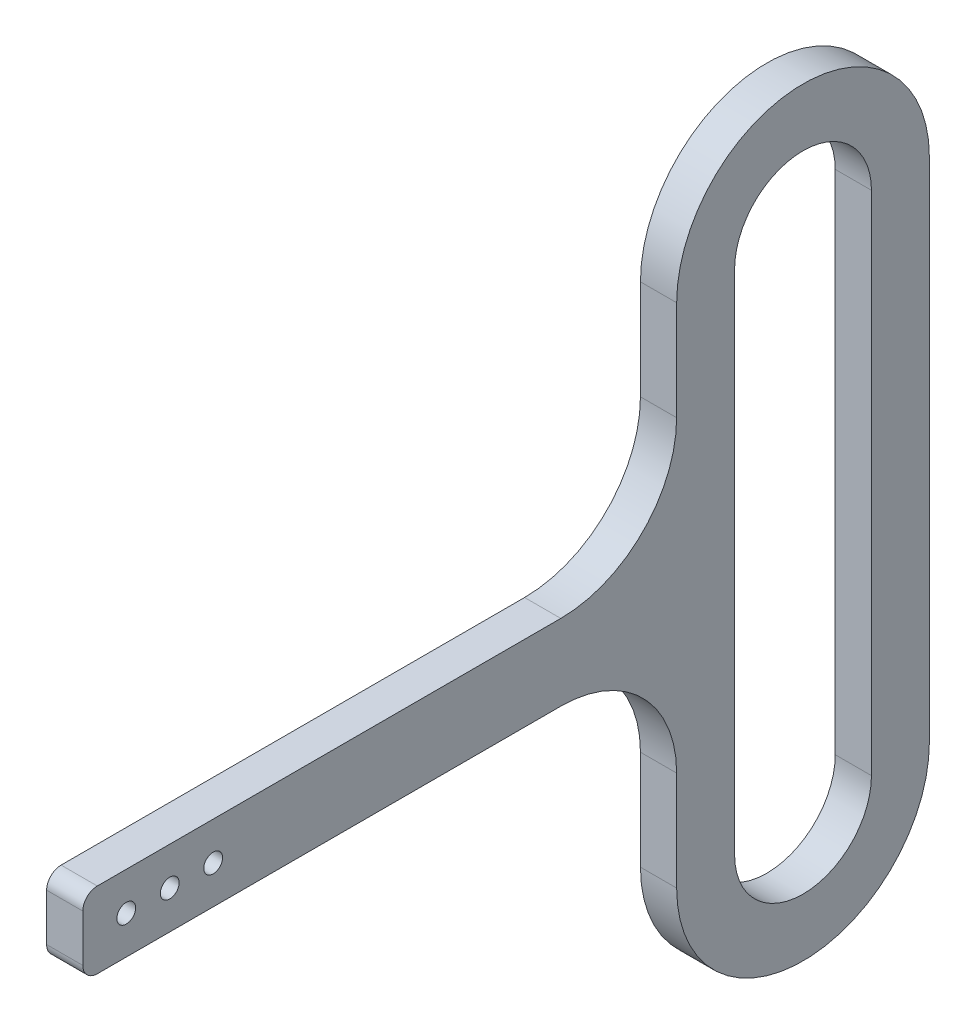
SolidWorks part; units mm, degrees
ref_plane "Front Plane" through (0, 0, 0) normal (0, 0, 1) x (1, 0, 0)
ref_plane "Top Plane" through (0, 0, 0) normal (0, 1, 0) x (1, 0, 0)
ref_plane "Right Plane" through (0, 0, 0) normal (1, 0, 0) x (0, 0, -1)
sketch "Sketch2" plane through (0, 0, 0) normal (1, 0, 0) x (0, 0, -1)
  line L0 (-22.16, -44.45) -> (-22.16, 44.45)
  line L1 (0, -44.45) -> (0, 44.45) construction
  line L2 (-12, -44.45) -> (-12, 44.45)
  line L3 (12, -44.45) -> (12, 44.45)
  line L4 (22.16, -44.45) -> (22.16, 44.45)
  line L5 (0, 0) -> (-80.0365, 0) construction
  line L6 (-22.16, -6.6675) -> (-126.3, -6.6675)
  line L7 (-22.16, 0) -> (-126.3, 0) construction
  line L8 (-22.16, 0) -> (-22.16, 6.6675)
  line L9 (-22.16, 6.6675) -> (-126.3, 6.6675)
  line L10 (-126.3, -6.6675) -> (-126.3, 6.6675)
  line L11 (-126.3, 0) -> (-118.68, 0) construction
  arc A0 (-12, -44.45) -> (12, -44.45) centre (0, -44.45) ccw
  arc A1 (12, 44.45) -> (-12, 44.45) centre (0, 44.45) ccw
  arc A2 (22.16, 44.45) -> (-22.16, 44.45) centre (0, 44.45) ccw
  arc A3 (-22.16, -44.45) -> (22.16, -44.45) centre (0, -44.45) ccw
  circle A4 centre (-118.68, 0) radius 1.651
  circle A6 centre (-111.06, 0) radius 1.651
  circle A7 centre (-103.44, 0) radius 1.651
  point P5 (0, 0)
  point P16 (-40.0182, 0)
  dimension "D2" = 12
  dimension "D7" = 3.302
  dimension "D1" = 88.9
  dimension "D4" = 104.14
  dimension "D5" = 13.335
  dimension "D6" = 7.62
  dimension "D3" = 10.16
  dimension "D8" = 3
extrude "Boss-Extrude2" add sketch "Sketch2" along normal blind 6.35 contours L10 L6 L0 L9 | L0 A3 L4 A2 A1 L3 A0 L2
sketch "Sketch3" plane through (0, 0, 126.3) normal (0, 0, 1) x (1, 0, 0)
  line L0 (0, 0) -> (6.35, 0) construction
  line L1 (0, -6.6675) -> (0, 6.6675) construction
  line L2 (6.35, -6.6675) -> (6.35, 6.6675) construction
  line L7 (0, 6.6675) -> (0, -6.6675)
  line L8 (0, -6.6675) -> (6.35, -6.6675)
  line L9 (6.35, -6.6675) -> (6.35, 6.6675)
  line L10 (6.35, 6.6675) -> (0, 6.6675)
  line L11 (0, 6.6675) -> (0, -6.6675)
  line L12 (0, -6.6675) -> (6.35, -6.6675)
  line L13 (6.35, -6.6675) -> (6.35, 6.6675)
  line L14 (6.35, 6.6675) -> (0, 6.6675)
  circle A1 centre (-7.3025, 0) radius 13.6525 construction
  circle A2 centre (-7.3025, 0) radius 8.89
  dimension "D1" = 27.305
  dimension "D3" = 17.78
  dimension "D2" = 0
extrude "Cut-Extrude3" [suppressed] cut sketch "Sketch3" against normal blind 16.51
sketch "Sketch4" plane through (0, 0, 0) normal (-1, 0, 0) x (0, 0, 1)
  line L1 (-69.1853, 78.6449) -> (69.1853, 78.6449)
  line L2 (-69.1853, 78.6449) -> (-69.1853, -78.6449)
  line L3 (-69.1853, -78.6449) -> (69.1853, -78.6449)
  line L4 (69.1853, 78.6449) -> (69.1853, -78.6449)
  line L5 (-69.1853, 78.6449) -> (69.1853, -78.6449) construction
  line L6 (-69.1853, -78.6449) -> (69.1853, 78.6449) construction
  point P0 (0, 0)
extrude "Cut-Extrude4" [suppressed] cut sketch "Sketch4" against normal blind 8.89
chamfer "Chamfer1" [suppressed] distance 10 angle 74
fillet "Fillet2" radius 20.32 2 edges at (3.175, -6.6675, 22.16) (3.175, 6.6675, 22.16)
fillet "Fillet3" radius 2.54 2 edges at (3.175, -6.6675, 126.3) (3.175, 6.6675, 126.3)
